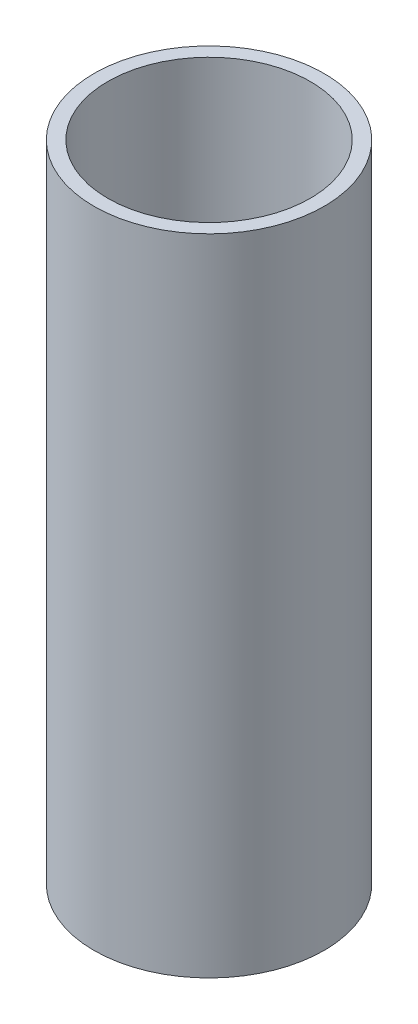
SolidWorks part; units mm, degrees
ref_plane "정면" through (0, 0, 0) normal (0, 0, 1) x (1, 0, 0)
ref_plane "윗면" through (0, 0, 0) normal (0, 1, 0) x (1, 0, 0)
ref_plane "우측면" through (0, 0, 0) normal (1, 0, 0) x (0, 0, -1)
sketch "스케치1" plane through (0, 0, 0) normal (0, 1, 0) x (1, 0, 0)
  circle A0 centre (0, 0) radius 25
  circle A1 centre (0, 0) radius 22
  dimension "D1" = 50
  dimension "D2" = 3
extrude "보스-돌출1" add sketch "스케치1" along normal blind 140
